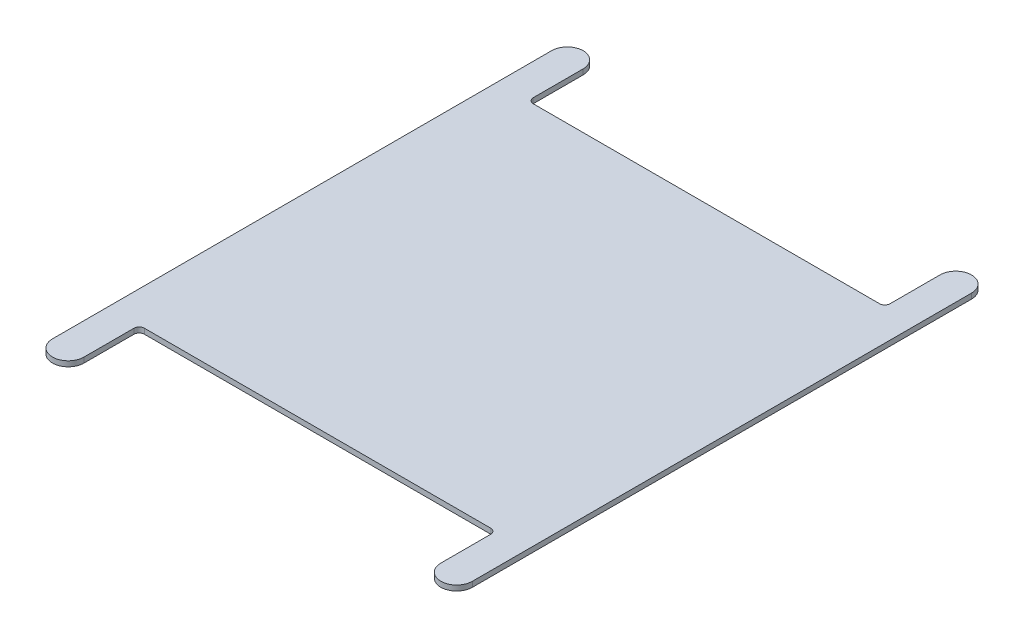
SolidWorks part; units mm, degrees
ref_plane "Front Plane" through (0, 0, 0) normal (0, 0, 1) x (1, 0, 0)
ref_plane "Top Plane" through (0, 0, 0) normal (0, 1, 0) x (1, 0, 0)
ref_plane "Right Plane" through (0, 0, 0) normal (1, 0, 0) x (0, 0, -1)
sketch "Sketch1" plane through (0, 144.9046, 0) normal (0, -1, 0) x (-1, 0, 0)
  line L15 (-107.8231, -1103.0503) -> (0, -1103.0503) construction
  line L16 (-107.8231, -1069.7128) -> (-107.8231, -1103.0503) construction
  line L17 (-126.8731, -1371.3378) -> (-126.8731, -1069.7128) construction
  line L18 (0, -1338.0003) -> (-107.8231, -1338.0003) construction
  line L19 (-107.8231, -1338.0003) -> (-107.8231, -1371.3378) construction
  line L20 (-107.8231, -1103.0503) -> (0, -1103.0503)
  line L21 (-107.8231, -1069.7128) -> (-107.8231, -1103.0503)
  line L22 (-126.8731, -1371.3378) -> (-126.8731, -1069.7128)
  line L23 (0, -1338.0003) -> (-107.8231, -1338.0003)
  line L24 (-107.8231, -1338.0003) -> (-107.8231, -1371.3378)
  line L25 (0, -1103.0503) -> (0, -1338.0003)
  circle A0 centre (-117.3481, -1069.7128) radius 9.525 construction
  circle A1 centre (-117.3481, -1371.3378) radius 9.525 construction
  arc A2 (-107.8231, -1069.7128) -> (-126.8731, -1069.7128) centre (-117.3481, -1069.7128) ccw
  arc A3 (-126.8731, -1371.3378) -> (-107.8231, -1371.3378) centre (-117.3481, -1371.3378) ccw
extrude "Boss-Extrude1" add sketch "Sketch1" along normal up to vertex (16.002 mm away) from vertex at 12.827
mirror "Mirror1" about plane through (0, 0, 0) normal (1, 0, 0) of bodies 101
fillet "Fillet1" radius 3.175 4 edges at (-107.8231, 130.4901, 1103.0503) (-107.8231, 130.4901, 1338.0003) (107.8231, 130.4901, 1338.0003) (107.8231, 130.4901, 1103.0503)
